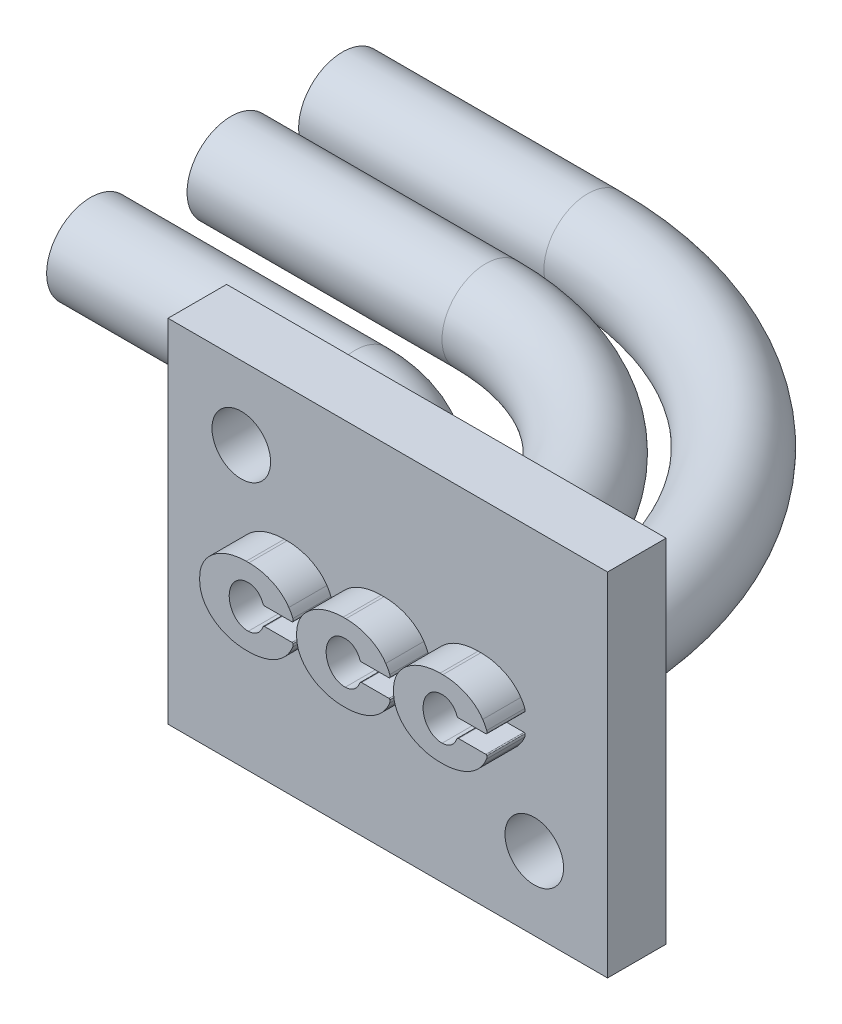
SolidWorks part; units mm, degrees
ref_plane "Front Plane" through (0, 0, 0) normal (0, 0, 1) x (1, 0, 0)
ref_plane "Top Plane" through (0, 0, 0) normal (0, 1, 0) x (1, 0, 0)
ref_plane "Right Plane" through (0, 0, 0) normal (1, 0, 0) x (0, 0, -1)
sketch "Sketch1" plane through (0, 0, 0) normal (0, 0, 1) x (1, 0, 0)
  line L1 (-7.5, 6) -> (7.5, 6)
  line L2 (-7.5, 6) -> (-7.5, -6)
  line L3 (-7.5, -6) -> (7.5, -6)
  line L4 (7.5, 6) -> (7.5, -6)
  line L5 (-7.5, 6) -> (7.5, -6) construction
  line L6 (-7.5, -6) -> (7.5, 6) construction
  point P0 (0, 0)
  dimension "D1" = 15
  dimension "D2" = 12
extrude "Boss-Extrude1" add sketch "Sketch1" along normal blind 2
sketch "Sketch2" plane through (0, 0, 2) normal (0, 0, 1) x (1, 0, 0)
  line L0 (0.4072, 0.4423) -> (1.3431, 0.4423)
  line L1 (-0.1301, 1.4531) -> (-0.2238, 1.4531)
  line L2 (-1.8094, 0.2019) -> (-1.8094, 0.0718)
  line L3 (-0.2238, -1.1794) -> (-0.1301, -1.1794)
  line L4 (1.3385, -0.1647) -> (0.4072, -0.1647)
  line L5 (-2.9011, 0.4423) -> (-1.9652, 0.4423)
  line L6 (-3.4384, 1.4531) -> (-3.5321, 1.4531)
  line L7 (-5.1177, 0.2019) -> (-5.1177, 0.0718)
  line L8 (-3.5321, -1.1794) -> (-3.4384, -1.1794)
  line L9 (-1.9698, -0.1647) -> (-2.9011, -0.1647)
  line L10 (3.7155, 0.4423) -> (4.6514, 0.4423)
  line L11 (3.1782, 1.4531) -> (3.0846, 1.4531)
  line L12 (1.4989, 0.2019) -> (1.4989, 0.0718)
  line L13 (3.0846, -1.1794) -> (3.1782, -1.1794)
  line L14 (4.6469, -0.1647) -> (3.7155, -0.1647)
  arc A0 (0.3456, 0.4859) -> (0.4072, 0.4423) centre (0.4072, 0.5078) ccw
  arc A1 (1.3431, 0.4423) -> (1.3723, 0.4672) centre (1.3386, 0.4772) ccw
  arc A2 (1.3723, 0.4672) -> (1.3681, 0.5547) centre (1.1917, 0.5024) ccw
  arc A3 (1.3681, 0.5547) -> (1.231, 0.812) centre (0.2861, 0.1431) ccw
  arc A4 (1.231, -0.5382) -> (1.3634, -0.2919) centre (0.2955, 0.1234) ccw
  arc A5 (1.3634, -0.2919) -> (1.3732, -0.1939) centre (1.1919, -0.2252) ccw
  arc A6 (1.3732, -0.1939) -> (1.3385, -0.1647) centre (1.3385, -0.1999) ccw
  arc A7 (0.4072, -0.1647) -> (0.3456, -0.2083) centre (0.4072, -0.2302) ccw
  arc A8 (-2.9627, 0.4859) -> (-2.9011, 0.4423) centre (-2.9011, 0.5078) ccw
  arc A9 (-1.9652, 0.4423) -> (-1.936, 0.4672) centre (-1.9697, 0.4772) ccw
  arc A10 (-1.936, 0.4672) -> (-1.9402, 0.5547) centre (-2.1166, 0.5024) ccw
  arc A11 (-1.9402, 0.5547) -> (-2.0773, 0.812) centre (-3.0222, 0.1431) ccw
  arc A12 (-2.0773, -0.5382) -> (-1.9449, -0.2919) centre (-3.0128, 0.1234) ccw
  arc A13 (-1.9449, -0.2919) -> (-1.9351, -0.1939) centre (-2.1164, -0.2252) ccw
  arc A14 (-1.9351, -0.1939) -> (-1.9698, -0.1647) centre (-1.9698, -0.1999) ccw
  arc A15 (-2.9011, -0.1647) -> (-2.9627, -0.2083) centre (-2.9011, -0.2302) ccw
  arc A16 (3.6539, 0.4859) -> (3.7155, 0.4423) centre (3.7155, 0.5078) ccw
  arc A17 (4.6514, 0.4423) -> (4.6806, 0.4672) centre (4.6469, 0.4772) ccw
  arc A18 (4.6806, 0.4672) -> (4.6764, 0.5547) centre (4.5, 0.5024) ccw
  arc A19 (4.6764, 0.5547) -> (4.5393, 0.812) centre (3.5944, 0.1431) ccw
  arc A20 (4.5393, -0.5382) -> (4.6717, -0.2919) centre (3.6038, 0.1234) ccw
  arc A21 (4.6717, -0.2919) -> (4.6815, -0.1939) centre (4.5002, -0.2252) ccw
  arc A22 (4.6815, -0.1939) -> (4.6469, -0.1647) centre (4.6469, -0.1999) ccw
  arc A23 (3.7155, -0.1647) -> (3.6539, -0.2083) centre (3.7155, -0.2302) ccw
  ellipse E0 centre (-0.1827, 0.137) end of major axis (-0.1791, -0.5801) minor radius 0.6209 (-0.2107, 0.8534) -> (-0.1509, -0.5792) ccw
  ellipse E1 centre (-0.2388, 0.137) end of major axis (0.0439, 0.8186) minor radius 0.6039 (0.3456, 0.4859) -> (-0.2107, 0.8534) ccw
  ellipse E2 centre (-0.2522, 0.1514) end of major axis (1.3906, 0.3966) minor radius 1.2925 (1.231, 0.812) -> (-0.1301, 1.4531) ccw
  ellipse E3 centre (-0.1614, 0.1527) end of major axis (-1.8063, 0.2821) minor radius 1.2979 (-0.2238, 1.4531) -> (-1.8094, 0.2019) ccw
  ellipse E4 centre (-0.1614, 0.121) end of major axis (1.4835, 0.2504) minor radius 1.2979 (-1.8094, 0.0718) -> (-0.2238, -1.1794) ccw
  ellipse E5 centre (-0.2522, 0.1223) end of major axis (-1.895, 0.3674) minor radius 1.2925 (-0.1301, -1.1794) -> (1.231, -0.5382) ccw
  ellipse E6 centre (-0.2388, 0.1406) end of major axis (0.0439, -0.541) minor radius 0.6039 (-0.1509, -0.5792) -> (0.3456, -0.2083) ccw
  ellipse E7 centre (-3.5471, 0.137) end of major axis (-3.2644, 0.8186) minor radius 0.6039 (-2.9627, 0.4859) -> (-3.519, 0.8534) ccw
  ellipse E8 centre (-3.5605, 0.1514) end of major axis (-1.9177, 0.3966) minor radius 1.2925 (-2.0773, 0.812) -> (-3.4384, 1.4531) ccw
  ellipse E9 centre (-3.4697, 0.1527) end of major axis (-5.1146, 0.2821) minor radius 1.2979 (-3.5321, 1.4531) -> (-5.1177, 0.2019) ccw
  ellipse E10 centre (-3.4697, 0.121) end of major axis (-1.8248, 0.2504) minor radius 1.2979 (-5.1177, 0.0718) -> (-3.5321, -1.1794) ccw
  ellipse E11 centre (-3.5605, 0.1223) end of major axis (-1.9177, -0.1229) minor radius 1.2925 (-3.4384, -1.1794) -> (-2.0773, -0.5382) ccw
  ellipse E12 centre (-3.5471, 0.1406) end of major axis (-3.8297, 0.8222) minor radius 0.6039 (-3.4592, -0.5792) -> (-2.9627, -0.2083) ccw
  ellipse E13 centre (-3.491, 0.137) end of major axis (-3.4946, 0.8541) minor radius 0.6209 (-3.519, 0.8534) -> (-3.4592, -0.5792) ccw
  ellipse E14 centre (3.1256, 0.137) end of major axis (3.1292, -0.5801) minor radius 0.6209 (3.0976, 0.8534) -> (3.1574, -0.5792) ccw
  ellipse E15 centre (3.0695, 0.137) end of major axis (3.3522, 0.8186) minor radius 0.6039 (3.6539, 0.4859) -> (3.0976, 0.8534) ccw
  ellipse E16 centre (3.0561, 0.1514) end of major axis (4.6989, 0.3966) minor radius 1.2925 (4.5393, 0.812) -> (3.1782, 1.4531) ccw
  ellipse E17 centre (3.1469, 0.1527) end of major axis (1.502, 0.2821) minor radius 1.2979 (3.0846, 1.4531) -> (1.4989, 0.2019) ccw
  ellipse E18 centre (3.1469, 0.121) end of major axis (4.7918, 0.2504) minor radius 1.2979 (1.4989, 0.0718) -> (3.0846, -1.1794) ccw
  ellipse E19 centre (3.0561, 0.1223) end of major axis (1.4133, 0.3674) minor radius 1.2925 (3.1782, -1.1794) -> (4.5393, -0.5382) ccw
  ellipse E20 centre (3.0695, 0.1406) end of major axis (3.3522, -0.541) minor radius 0.6039 (3.1574, -0.5792) -> (3.6539, -0.2083) ccw
extrude "Boss-Extrude2" add sketch "Sketch2" along normal blind 2
sketch "Sketch3" plane through (0, 0, 0) normal (0, 1, 0) x (1, 0, 0)
  line L0 (7.5, 0) -> (-7.5, 0) construction
  line L1 (2.7287, 0) -> (4.2287, 0)
  line L2 (2.7287, 0) -> (2.7287, 12.6)
  line L3 (-3.864, -2) -> (-3.864, 5.3789) construction
  line L4 (4.2287, 0) -> (4.2287, 14.1)
  line L5 (-4.614, 0) -> (-3.114, 0)
  line L6 (-4.614, 0) -> (-4.614, 4)
  line L7 (-0.1926, -2) -> (-0.1926, 4.6797) construction
  line L8 (-3.114, 0) -> (-3.114, 4)
  line L9 (-3.114, 4) -> (-4.614, 4)
  line L10 (-0.9426, 0) -> (0.5574, 0)
  line L13 (-0.9426, 0) -> (-0.9426, 8.6)
  line L14 (3.4787, -2) -> (3.4787, 2.787) construction
  line L15 (0.5574, 0) -> (0.5574, 10.1)
  line L16 (0.5574, 10.1) -> (-2.6426, 10.1)
  line L17 (-2.4226, 14.1) -> (4.2287, 14.1)
  line L18 (-0.9426, 8.6) -> (-2.6426, 8.6)
  line L19 (-2.6426, 10.1) -> (-2.6426, 8.6)
  line L20 (-2.4226, 14.1) -> (-2.4226, 12.6)
  line L21 (-2.4226, 12.6) -> (2.7287, 12.6)
  dimension "D1" = 1.5
  dimension "D2" = 4
  dimension "D3" = 1.5
  dimension "D4" = 1.5
  dimension "D5" = 4.6
  dimension "D6" = 1.5
  dimension "D7" = 2.5
  dimension "D8" = 1.5
  dimension "D9" = 1.7
  dimension "D10" = 3.4787
  dimension "D11" = 0.1926
  dimension "D12" = 3.864
extrude "Boss-Extrude3" add sketch "Sketch3" along normal mid plane 4
sketch "Sketch4" [suppressed] plane through (0, 2, 0) normal (0, 1, 0) x (1, 0, 0)
  line L1 (-2.4226, 10.1) -> (-2.4226, 8.6) construction
  line L2 (-2.894, 4) -> (-11.894, 4)
  line L3 (-2.894, 4) -> (-2.894, 5.5)
  line L4 (-2.894, 5.5) -> (-11.894, 5.5)
  line L5 (-11.894, 4) -> (-11.894, 5.5)
  dimension "D1" = 9
extrude "Boss-Extrude4" [suppressed] add sketch "Sketch4" against normal up to surface (4 mm away)
sketch "Sketch5" [suppressed] plane through (-2.4226, 0, 0) normal (-1, 0, 0) x (0, 0, 1)
  line L4 (-10.1, -2) -> (-8.6, -2)
  line L5 (-8.6, -2) -> (-8.6, 2)
  line L6 (-8.6, 2) -> (-10.1, 2)
  line L7 (-10.1, 2) -> (-10.1, -2)
  line L8 (-10.1, -2) -> (-8.6, -2)
  line L9 (-8.6, -2) -> (-8.6, 2)
  line L10 (-8.6, 2) -> (-10.1, 2)
  line L11 (-10.1, 2) -> (-10.1, -2)
  line L12 (-14.1, -2) -> (-12.6, -2)
  line L13 (-12.6, -2) -> (-12.6, 2)
  line L14 (-12.6, 2) -> (-14.1, 2)
  line L15 (-14.1, 2) -> (-14.1, -2)
  line L16 (-14.1, -2) -> (-12.6, -2)
  line L17 (-12.6, -2) -> (-12.6, 2)
  line L18 (-12.6, 2) -> (-14.1, 2)
  line L19 (-14.1, 2) -> (-14.1, -2)
  dimension "D1" = 0
  dimension "D2" = 0
extrude "Boss-Extrude5" [suppressed] add sketch "Sketch5" along normal up to surface (9.4714 mm away)
sketch "Sketch6" plane through (0, 0, 0) normal (0, 0, -1) x (-1, 0, 0)
  line L0 (-4.2287, 0) -> (-2.7287, 0) construction
  line L1 (-4.2287, 2) -> (-4.2287, -2) construction
  line L2 (-2.7287, 2) -> (-2.7287, -2) construction
  line L3 (-0.5574, 0) -> (0.9426, 0) construction
  line L4 (-0.5574, 2) -> (-0.5574, -2) construction
  line L5 (0.9426, 2) -> (0.9426, -2) construction
  line L6 (3.114, 0) -> (4.614, 0) construction
  line L7 (3.114, 2) -> (3.114, -2) construction
  line L8 (4.614, 2) -> (4.614, -2) construction
  circle A0 centre (-3.4787, 0) radius 1.5
  dimension "D1" = 3
sketch "Sketch7" plane through (0, 0, 0) normal (0, 0, -1) x (-1, 0, 0)
  circle A0 centre (0, 0) radius 1.5
  dimension "D1" = 3
sketch "Sketch8" plane through (0, 0, 0) normal (0, 0, -1) x (-1, 0, 0)
  line L0 (3.114, 0) -> (4.614, 0) construction
  circle A0 centre (3.864, 0) radius 1.5
  dimension "D1" = 3
sketch "Sketch9" plane through (0, 0, 0) normal (0, 1, 0) x (1, 0, 0)
  line L0 (-3.864, 0) -> (-3.864, 0.75)
  line L1 (-3.114, 0) -> (-4.614, 0) construction
  line L2 (-7.864, 4.75) -> (-16.894, 4.75)
  arc A0 (-3.864, 0.75) -> (-7.864, 4.75) centre (-7.864, 0.75) ccw
  point P7 (-3.864, 4.75)
  dimension "D3" = 4
  dimension "D1" = 4.75
  dimension "D2" = 13.03
sketch "Sketch10" plane through (0, 0, 0) normal (0, 1, 0) x (1, 0, 0)
  line L0 (-0.1926, 0) -> (-0.1926, 1.35)
  line L1 (0.5574, 0) -> (-0.9426, 0) construction
  line L2 (-8.1926, 9.35) -> (-16.894, 9.35)
  arc A0 (-0.1926, 1.35) -> (-8.1926, 9.35) centre (-8.1926, 1.35) ccw
  point P7 (-0.1926, 9.35)
  dimension "D3" = 8
  dimension "D1" = 16.7014
  dimension "D2" = 9.35
sketch "Sketch11" plane through (0, 0, 0) normal (0, 1, 0) x (1, 0, 0)
  line L0 (3.4787, 0) -> (3.4787, 1.35)
  line L1 (4.2287, 0) -> (2.7287, 0) construction
  line L2 (-8.5213, 13.35) -> (-16.894, 13.35)
  arc A0 (3.4787, 1.35) -> (-8.5213, 13.35) centre (-8.5213, 1.35) ccw
  point P7 (3.4787, 13.35)
  dimension "D3" = 12
  dimension "D1" = 13.35
  dimension "D2" = 20.3728
sketch "Sketch12" plane through (7.5, 0, 0) normal (1, 0, 0) x (0, 0, -1)
  line L1 (0, -6) -> (14.1, -6)
  line L2 (0, -6) -> (0, 2)
  line L3 (0, 2) -> (14.1, 2)
  line L4 (14.1, -6) -> (14.1, 2)
extrude "Cut-Extrude1" cut sketch "Sketch12" against normal through all
sweep "Sweep1" add profiles "Sketch8" path "Sketch9"
sweep "Sweep2" add profiles "Sketch7" path "Sketch10"
sweep "Sweep3" add profiles "Sketch6" path "Sketch11"
sketch "Sketch13" plane through (0, 0, 0) normal (0, 0, -1) x (-1, 0, 0)
  line L0 (-7.5, 6) -> (7.5, 6) construction
  line L1 (7.5, 6) -> (7.5, -6) construction
  line L2 (7.5, -6) -> (-7.5, -6) construction
  line L3 (-7.5, -6) -> (-7.5, 6) construction
  circle A0 centre (-5, -3.5) radius 1
  circle A1 centre (5, 3.5) radius 1
  dimension "D5" = 2
  dimension "D1" = 2.5
  dimension "D2" = 2.5
  dimension "D3" = 2.5
  dimension "D4" = 2.5
extrude "Cut-Extrude2" cut sketch "Sketch13" against normal through all
sketch "Sketch15" plane through (0, 0, 4) normal (0, 0, 1) x (1, 0, 0)
  line L0 (0.4072, 0.4423) -> (1.3431, 0.4423) construction
  line L1 (-0.1301, 1.4531) -> (-0.2238, 1.4531) construction
  line L2 (-1.8094, 0.2019) -> (-1.8094, 0.0718) construction
  line L3 (-0.2238, -1.1794) -> (-0.1301, -1.1794) construction
  line L4 (1.3385, -0.1647) -> (0.4072, -0.1647) construction
  line L5 (-2.9011, 0.4423) -> (-1.9652, 0.4423)
  line L6 (-3.4384, 1.4531) -> (-3.5321, 1.4531)
  line L7 (-5.1177, 0.2019) -> (-5.1177, 0.0718)
  line L8 (-3.5321, -1.1794) -> (-3.4384, -1.1794)
  line L9 (-1.9698, -0.1647) -> (-2.9011, -0.1647)
  line L10 (-2.9011, 0.4423) -> (-1.9652, 0.4423)
  line L11 (-3.4384, 1.4531) -> (-3.5321, 1.4531)
  line L12 (-5.1177, 0.2019) -> (-5.1177, 0.0718)
  line L13 (-3.5321, -1.1794) -> (-3.4384, -1.1794)
  line L14 (-1.9698, -0.1647) -> (-2.9011, -0.1647)
  line L15 (3.7155, 0.4423) -> (4.6514, 0.4423) construction
  line L16 (3.1782, 1.4531) -> (3.0846, 1.4531) construction
  line L17 (1.4989, 0.2019) -> (1.4989, 0.0718) construction
  line L18 (3.0846, -1.1794) -> (3.1782, -1.1794) construction
  line L19 (4.6469, -0.1647) -> (3.7155, -0.1647) construction
  line L20 (0.4072, 0.4423) -> (1.3431, 0.4423)
  line L21 (-0.1301, 1.4531) -> (-0.2238, 1.4531)
  line L22 (-1.8094, 0.2019) -> (-1.8094, 0.0718)
  line L23 (-0.2238, -1.1794) -> (-0.1301, -1.1794)
  line L24 (1.3385, -0.1647) -> (0.4072, -0.1647)
  line L25 (3.7155, 0.4423) -> (4.6514, 0.4423)
  line L26 (3.1782, 1.4531) -> (3.0846, 1.4531)
  line L27 (1.4989, 0.2019) -> (1.4989, 0.0718)
  line L28 (3.0846, -1.1794) -> (3.1782, -1.1794)
  line L29 (4.6469, -0.1647) -> (3.7155, -0.1647)
  arc A0 (0.3456, 0.4859) -> (0.4072, 0.4423) centre (0.4072, 0.5078) ccw construction
  arc A1 (1.3431, 0.4423) -> (1.3723, 0.4672) centre (1.3386, 0.4772) ccw construction
  arc A2 (1.3723, 0.4672) -> (1.3681, 0.5547) centre (1.1917, 0.5024) ccw construction
  arc A3 (1.3681, 0.5547) -> (1.231, 0.812) centre (0.2861, 0.1431) ccw construction
  arc A4 (1.231, -0.5382) -> (1.3634, -0.2919) centre (0.2955, 0.1234) ccw construction
  arc A5 (1.3634, -0.2919) -> (1.3732, -0.1939) centre (1.1919, -0.2252) ccw construction
  arc A6 (1.3732, -0.1939) -> (1.3385, -0.1647) centre (1.3385, -0.1999) ccw construction
  arc A7 (0.4072, -0.1647) -> (0.3456, -0.2083) centre (0.4072, -0.2302) ccw construction
  arc A8 (-2.9627, 0.4859) -> (-2.9011, 0.4423) centre (-2.9011, 0.5078) ccw
  arc A9 (-1.9652, 0.4423) -> (-1.936, 0.4672) centre (-1.9697, 0.4772) ccw
  arc A10 (-1.936, 0.4672) -> (-1.9402, 0.5547) centre (-2.1166, 0.5024) ccw
  arc A11 (-1.9402, 0.5547) -> (-2.0773, 0.812) centre (-3.0222, 0.1431) ccw
  arc A12 (-2.0773, -0.5382) -> (-1.9449, -0.2919) centre (-3.0128, 0.1234) ccw
  arc A13 (-1.9449, -0.2919) -> (-1.9351, -0.1939) centre (-2.1164, -0.2252) ccw
  arc A14 (-1.9351, -0.1939) -> (-1.9698, -0.1647) centre (-1.9698, -0.1999) ccw
  arc A15 (-2.9011, -0.1647) -> (-2.9627, -0.2083) centre (-2.9011, -0.2302) ccw
  arc A16 (-2.9627, 0.4859) -> (-2.9011, 0.4423) centre (-2.9011, 0.5078) ccw
  arc A17 (-1.9652, 0.4423) -> (-1.936, 0.4672) centre (-1.9697, 0.4772) ccw
  arc A18 (-1.936, 0.4672) -> (-1.9402, 0.5547) centre (-2.1166, 0.5024) ccw
  arc A19 (-1.9402, 0.5547) -> (-2.0773, 0.812) centre (-3.0222, 0.1431) ccw
  arc A20 (-2.0773, -0.5382) -> (-1.9449, -0.2919) centre (-3.0128, 0.1234) ccw
  arc A21 (-1.9449, -0.2919) -> (-1.9351, -0.1939) centre (-2.1164, -0.2252) ccw
  arc A22 (-1.9351, -0.1939) -> (-1.9698, -0.1647) centre (-1.9698, -0.1999) ccw
  arc A23 (-2.9011, -0.1647) -> (-2.9627, -0.2083) centre (-2.9011, -0.2302) ccw
  arc A24 (3.6539, 0.4859) -> (3.7155, 0.4423) centre (3.7155, 0.5078) ccw construction
  arc A25 (4.6514, 0.4423) -> (4.6806, 0.4672) centre (4.6469, 0.4772) ccw construction
  arc A26 (4.6806, 0.4672) -> (4.6764, 0.5547) centre (4.5, 0.5024) ccw construction
  arc A27 (4.6764, 0.5547) -> (4.5393, 0.812) centre (3.5944, 0.1431) ccw construction
  arc A28 (4.5393, -0.5382) -> (4.6717, -0.2919) centre (3.6038, 0.1234) ccw construction
  arc A29 (4.6717, -0.2919) -> (4.6815, -0.1939) centre (4.5002, -0.2252) ccw construction
  arc A30 (4.6815, -0.1939) -> (4.6469, -0.1647) centre (4.6469, -0.1999) ccw construction
  arc A31 (3.7155, -0.1647) -> (3.6539, -0.2083) centre (3.7155, -0.2302) ccw construction
  arc A32 (0.3456, 0.4859) -> (0.4072, 0.4423) centre (0.4072, 0.5078) ccw
  arc A33 (1.3431, 0.4423) -> (1.3723, 0.4672) centre (1.3386, 0.4772) ccw
  arc A34 (1.3723, 0.4672) -> (1.3681, 0.5547) centre (1.1917, 0.5024) ccw
  arc A35 (1.3681, 0.5547) -> (1.231, 0.812) centre (0.2861, 0.1431) ccw
  arc A36 (1.231, -0.5382) -> (1.3634, -0.2919) centre (0.2955, 0.1234) ccw
  arc A37 (1.3634, -0.2919) -> (1.3732, -0.1939) centre (1.1919, -0.2252) ccw
  arc A38 (1.3732, -0.1939) -> (1.3385, -0.1647) centre (1.3385, -0.1999) ccw
  arc A39 (0.4072, -0.1647) -> (0.3456, -0.2083) centre (0.4072, -0.2302) ccw
  arc A40 (3.6539, 0.4859) -> (3.7155, 0.4423) centre (3.7155, 0.5078) ccw
  arc A41 (4.6514, 0.4423) -> (4.6806, 0.4672) centre (4.6469, 0.4772) ccw
  arc A42 (4.6806, 0.4672) -> (4.6764, 0.5547) centre (4.5, 0.5024) ccw
  arc A43 (4.6764, 0.5547) -> (4.5393, 0.812) centre (3.5944, 0.1431) ccw
  arc A44 (4.5393, -0.5382) -> (4.6717, -0.2919) centre (3.6038, 0.1234) ccw
  arc A45 (4.6717, -0.2919) -> (4.6815, -0.1939) centre (4.5002, -0.2252) ccw
  arc A46 (4.6815, -0.1939) -> (4.6469, -0.1647) centre (4.6469, -0.1999) ccw
  arc A47 (3.7155, -0.1647) -> (3.6539, -0.2083) centre (3.7155, -0.2302) ccw
  ellipse E0 centre (-0.2388, 0.137) end of major axis (-0.5214, -0.5446) minor radius 0.6039 (0.3456, 0.4859) -> (-0.2107, 0.8534) ccw construction
  ellipse E1 centre (-0.2522, 0.1514) end of major axis (1.3906, 0.3966) minor radius 1.2925 (1.231, 0.812) -> (-0.1301, 1.4531) ccw construction
  ellipse E2 centre (-0.1614, 0.1527) end of major axis (-1.8063, 0.2821) minor radius 1.2979 (-0.2238, 1.4531) -> (-1.8094, 0.2019) ccw construction
  ellipse E3 centre (-0.1614, 0.121) end of major axis (1.4835, 0.2504) minor radius 1.2979 (-1.8094, 0.0718) -> (-0.2238, -1.1794) ccw construction
  ellipse E4 centre (-0.2522, 0.1223) end of major axis (-1.895, 0.3674) minor radius 1.2925 (-0.1301, -1.1794) -> (1.231, -0.5382) ccw construction
  ellipse E5 centre (-0.2388, 0.1406) end of major axis (0.0439, -0.541) minor radius 0.6039 (-0.1509, -0.5792) -> (0.3456, -0.2083) ccw construction
  ellipse E6 centre (-0.1827, 0.137) end of major axis (-0.1791, -0.5801) minor radius 0.6209 (-0.2107, 0.8534) -> (-0.1509, -0.5792) ccw construction
  ellipse E7 centre (-3.5471, 0.137) end of major axis (-3.8297, -0.5446) minor radius 0.6039 (-2.9627, 0.4859) -> (-3.519, 0.8534) ccw
  ellipse E8 centre (-3.5605, 0.1514) end of major axis (-5.2033, -0.0937) minor radius 1.2925 (-2.0773, 0.812) -> (-3.4384, 1.4531) ccw
  ellipse E9 centre (-3.4697, 0.1527) end of major axis (-5.1146, 0.2821) minor radius 1.2979 (-3.5321, 1.4531) -> (-5.1177, 0.2019) ccw
  ellipse E10 centre (-3.4697, 0.121) end of major axis (-1.8248, 0.2504) minor radius 1.2979 (-5.1177, 0.0718) -> (-3.5321, -1.1794) ccw
  ellipse E11 centre (-3.5605, 0.1223) end of major axis (-1.9177, -0.1229) minor radius 1.2925 (-3.4384, -1.1794) -> (-2.0773, -0.5382) ccw
  ellipse E12 centre (-3.5471, 0.1406) end of major axis (-3.2644, -0.541) minor radius 0.6039 (-3.4592, -0.5792) -> (-2.9627, -0.2083) ccw
  ellipse E13 centre (-3.491, 0.137) end of major axis (-3.4874, -0.5801) minor radius 0.6209 (-3.519, 0.8534) -> (-3.4592, -0.5792) ccw
  ellipse E14 centre (-3.5471, 0.137) end of major axis (-3.8297, -0.5446) minor radius 0.6039 (-2.9627, 0.4859) -> (-3.519, 0.8534) ccw
  ellipse E15 centre (-3.5605, 0.1514) end of major axis (-5.2033, -0.0937) minor radius 1.2925 (-2.0773, 0.812) -> (-3.4384, 1.4531) ccw
  ellipse E16 centre (-3.4697, 0.1527) end of major axis (-5.1146, 0.2821) minor radius 1.2979 (-3.5321, 1.4531) -> (-5.1177, 0.2019) ccw
  ellipse E17 centre (-3.4697, 0.121) end of major axis (-1.8248, 0.2504) minor radius 1.2979 (-5.1177, 0.0718) -> (-3.5321, -1.1794) ccw
  ellipse E18 centre (-3.5605, 0.1223) end of major axis (-5.2033, 0.3674) minor radius 1.2925 (-3.4384, -1.1794) -> (-2.0773, -0.5382) ccw
  ellipse E19 centre (-3.5471, 0.1406) end of major axis (-3.2644, -0.541) minor radius 0.6039 (-3.4592, -0.5792) -> (-2.9627, -0.2083) ccw
  ellipse E20 centre (-3.491, 0.137) end of major axis (-3.4874, -0.5801) minor radius 0.6209 (-3.519, 0.8534) -> (-3.4592, -0.5792) ccw
  ellipse E21 centre (3.0695, 0.137) end of major axis (2.7869, -0.5446) minor radius 0.6039 (3.6539, 0.4859) -> (3.0976, 0.8534) ccw construction
  ellipse E22 centre (3.0561, 0.1514) end of major axis (1.4133, -0.0937) minor radius 1.2925 (4.5393, 0.812) -> (3.1782, 1.4531) ccw construction
  ellipse E23 centre (3.1469, 0.1527) end of major axis (4.7918, 0.0234) minor radius 1.2979 (3.0846, 1.4531) -> (1.4989, 0.2019) ccw construction
  ellipse E24 centre (3.1469, 0.121) end of major axis (4.7918, 0.2504) minor radius 1.2979 (1.4989, 0.0718) -> (3.0846, -1.1794) ccw construction
  ellipse E25 centre (3.0561, 0.1223) end of major axis (1.4133, 0.3674) minor radius 1.2925 (3.1782, -1.1794) -> (4.5393, -0.5382) ccw construction
  ellipse E26 centre (3.0695, 0.1406) end of major axis (3.3522, -0.541) minor radius 0.6039 (3.1574, -0.5792) -> (3.6539, -0.2083) ccw construction
  ellipse E27 centre (3.1256, 0.137) end of major axis (3.1292, -0.5801) minor radius 0.6209 (3.0976, 0.8534) -> (3.1574, -0.5792) ccw construction
  ellipse E28 centre (-0.2388, 0.137) end of major axis (-0.5214, -0.5446) minor radius 0.6039 (0.3456, 0.4859) -> (-0.2107, 0.8534) ccw
  ellipse E29 centre (-0.2522, 0.1514) end of major axis (1.3906, 0.3966) minor radius 1.2925 (1.231, 0.812) -> (-0.1301, 1.4531) ccw
  ellipse E30 centre (-0.1614, 0.1527) end of major axis (-1.8063, 0.2821) minor radius 1.2979 (-0.2238, 1.4531) -> (-1.8094, 0.2019) ccw
  ellipse E31 centre (-0.1614, 0.121) end of major axis (1.4835, 0.2504) minor radius 1.2979 (-1.8094, 0.0718) -> (-0.2238, -1.1794) ccw
  ellipse E32 centre (-0.2522, 0.1223) end of major axis (-1.895, 0.3674) minor radius 1.2925 (-0.1301, -1.1794) -> (1.231, -0.5382) ccw
  ellipse E33 centre (-0.2388, 0.1406) end of major axis (0.0439, -0.541) minor radius 0.6039 (-0.1509, -0.5792) -> (0.3456, -0.2083) ccw
  ellipse E34 centre (-0.1827, 0.137) end of major axis (-0.1791, -0.5801) minor radius 0.6209 (-0.2107, 0.8534) -> (-0.1509, -0.5792) ccw
  ellipse E35 centre (3.0695, 0.137) end of major axis (2.7869, -0.5446) minor radius 0.6039 (3.6539, 0.4859) -> (3.0976, 0.8534) ccw
  ellipse E36 centre (3.0561, 0.1514) end of major axis (4.6989, 0.3966) minor radius 1.2925 (4.5393, 0.812) -> (3.1782, 1.4531) ccw
  ellipse E37 centre (3.1469, 0.1527) end of major axis (4.7918, 0.0234) minor radius 1.2979 (3.0846, 1.4531) -> (1.4989, 0.2019) ccw
  ellipse E38 centre (3.1469, 0.121) end of major axis (4.7918, 0.2504) minor radius 1.2979 (1.4989, 0.0718) -> (3.0846, -1.1794) ccw
  ellipse E39 centre (3.0561, 0.1223) end of major axis (1.4133, 0.3674) minor radius 1.2925 (3.1782, -1.1794) -> (4.5393, -0.5382) ccw
  ellipse E40 centre (3.0695, 0.1406) end of major axis (3.3522, -0.541) minor radius 0.6039 (3.1574, -0.5792) -> (3.6539, -0.2083) ccw
  ellipse E41 centre (3.1256, 0.137) end of major axis (3.1292, -0.5801) minor radius 0.6209 (3.0976, 0.8534) -> (3.1574, -0.5792) ccw
  dimension "D1" = 0
extrude "Cut-Extrude3" cut sketch "Sketch15" against normal blind 0.7
